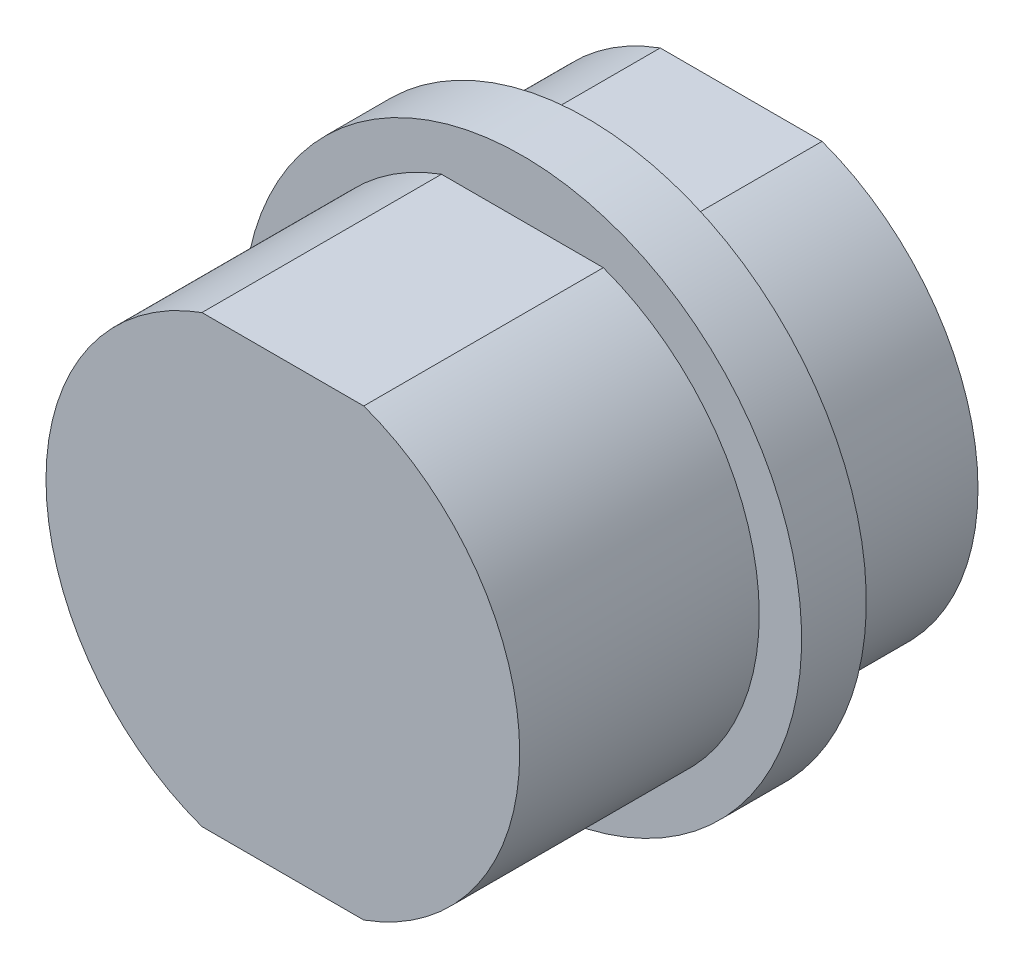
SolidWorks part; units mm, degrees
ref_plane "Front Plane" through (0, 0, 0) normal (0, 0, 1) x (1, 0, 0)
ref_plane "Top Plane" through (0, 0, 0) normal (0, 1, 0) x (1, 0, 0)
ref_plane "Right Plane" through (0, 0, 0) normal (1, 0, 0) x (0, 0, -1)
sketch "Sketch1" plane through (0, 0, 0) normal (0, 0, 1) x (1, 0, 0)
  circle A0 centre (0, 0) radius 7.8105
  dimension "D1" = 15.621
extrude "Boss-Extrude1" add sketch "Sketch1" along normal blind 15.113
sketch "Sketch2" plane through (0, 0, 15.113) normal (0, 0, 1) x (1, 0, 0)
  line L0 (-7.8105, 0) -> (7.8105, 0) construction
  line L1 (-7.4416, 8.6105) -> (7.4416, 8.6105)
  line L2 (-7.4416, 8.6105) -> (-7.4416, 7.3406)
  line L3 (-7.4416, 7.3406) -> (7.4416, 7.3406)
  line L4 (7.4416, 8.6105) -> (7.4416, 7.3406)
  line L5 (-7.4416, 8.6105) -> (7.4416, 7.3406) construction
  line L6 (-7.4416, 7.3406) -> (7.4416, 8.6105) construction
  line L7 (-7.4416, -7.3406) -> (7.4416, -8.6105) construction
  line L8 (-7.4416, -8.6105) -> (7.4416, -7.3406) construction
  line L9 (7.4416, -8.6105) -> (7.4416, -7.3406)
  line L10 (-7.4416, -7.3406) -> (7.4416, -7.3406)
  line L11 (-7.4416, -8.6105) -> (-7.4416, -7.3406)
  line L12 (-7.4416, -8.6105) -> (7.4416, -8.6105)
  circle A0 centre (0, 0) radius 7.8105 construction
  point P0 (0, 7.9755)
  point P15 (0, -7.9755)
  dimension "D1" = 7.3406
extrude "Cut-Extrude1" cut sketch "Sketch2" against normal through all
sketch "Sketch3" plane through (0, 0, 0) normal (0, 0, -1) x (-1, 0, 0)
  circle A0 centre (0, 0) radius 9.2075
  dimension "D1" = 18.415
extrude "Boss-Extrude2" add sketch "Sketch3" against normal blind 2.1336 from offset 5.08
